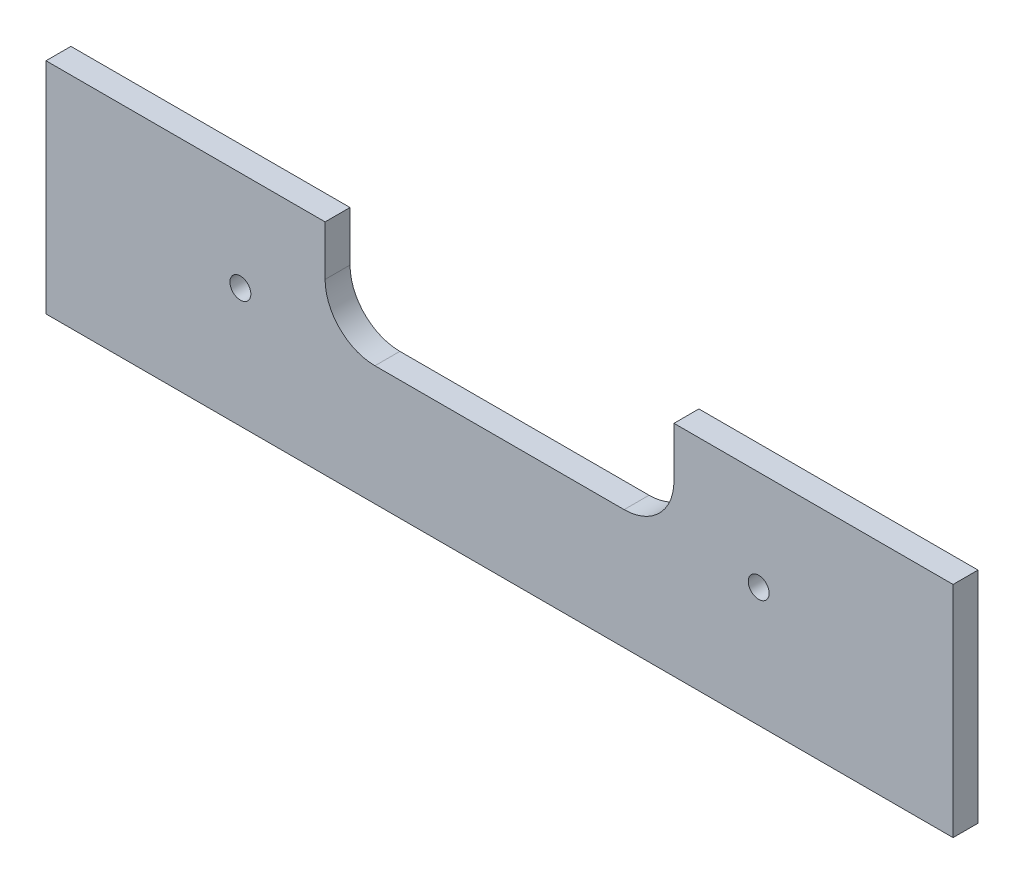
SolidWorks part; units mm, degrees
material "6061 Legierung"
ref_plane "Ebene vorne" through (0, 0, 0) normal (0, 0, 1) x (1, 0, 0)
ref_plane "Ebene oben" through (0, 0, 0) normal (0, 1, 0) x (1, 0, 0)
ref_plane "Ebene rechts" through (0, 0, 0) normal (1, 0, 0) x (0, 0, -1)
sketch "Skizze1" plane through (0, 0, 0) normal (0, 0, 1) x (1, 0, 0)
  line L1 (91, -25) -> (-91, -25)
  line L2 (91, -25) -> (91, 25)
  line L3 (91, 25) -> (-91, 25)
  line L4 (-91, -25) -> (-91, 25)
  line L5 (91, -25) -> (-91, 25) construction
  line L6 (91, 25) -> (-91, -25) construction
  point P0 (0, 0)
  dimension "D1" = 182
  dimension "D2" = 50
extrude "Aufsatz-Linear austragen1" add sketch "Skizze1" along normal blind 5
hole_wizard "M5 Gewindebohrung1" positions "Skizze2" profile "Skizze3" tap size "M5" standard "DIN"
sketch "Skizze2" plane through (0, 0, 5) normal (0, 0, 1) x (1, 0, 0)
  line L0 (0, 0) -> (0, 32.3969) construction
  line L1 (91, 25) -> (-91, 25) construction
  point P9 (-52, 5)
  point P13 (52, 5)
  dimension "D1" = 104
  dimension "D2" = 20
sketch "Skizze3" plane through (52, 5, 5) normal (1, 0, 0) x (0, -1, 0)
  line L0 (0, 0) -> (0, 15.2618)
  line L1 (0, 15.2618) -> (2.1, 14)
  line L2 (2.1, 14) -> (2.1, 0)
  line L5 (2.1, 0) -> (0, 0)
  line L10 (0, 15.2618) -> (-2.1, 14) construction
  line L11 (0, -6.35) -> (0, 107.95) construction
  dimension "Bohrerdurchmesser" = 4.2
  dimension "Bohrungstiefe" = 14
  dimension "Spitzenwinkel" = 118
cosmetic thread "Bohrungsgewinde1" parameters "D1"=5, "D2"=5
cosmetic thread "Bohrungsgewinde2" parameters "D1"=5, "D2"=5
sketch "Skizze4" plane through (0, 0, 5) normal (0, 0, 1) x (1, 0, 0)
  line L0 (0, 0) -> (0, 43.7726) construction
  line L1 (91, 25) -> (-91, 25) construction
  line L2 (-35, 25) -> (35, 25)
  line L3 (-35, 25) -> (-35, 5)
  line L4 (-35, 5) -> (35, 5)
  line L5 (35, 25) -> (35, 5)
  line L6 (-91, -25) -> (91, -25) construction
  line L7 (-91, -25) -> (91, -25)
  line L8 (-91, -25) -> (-91, -19)
  line L9 (-91, -19) -> (91, -19)
  line L10 (91, -25) -> (91, -19)
  dimension "D1" = 70
  dimension "D2" = 20
  dimension "D4" = 6
extrude "Schnitt-Linear austragen1" cut sketch "Skizze4" against normal blind 10
fillet "Verrundung2" radius 10 2 edges at (-35, 5, 2.5) (35, 5, 2.5)
